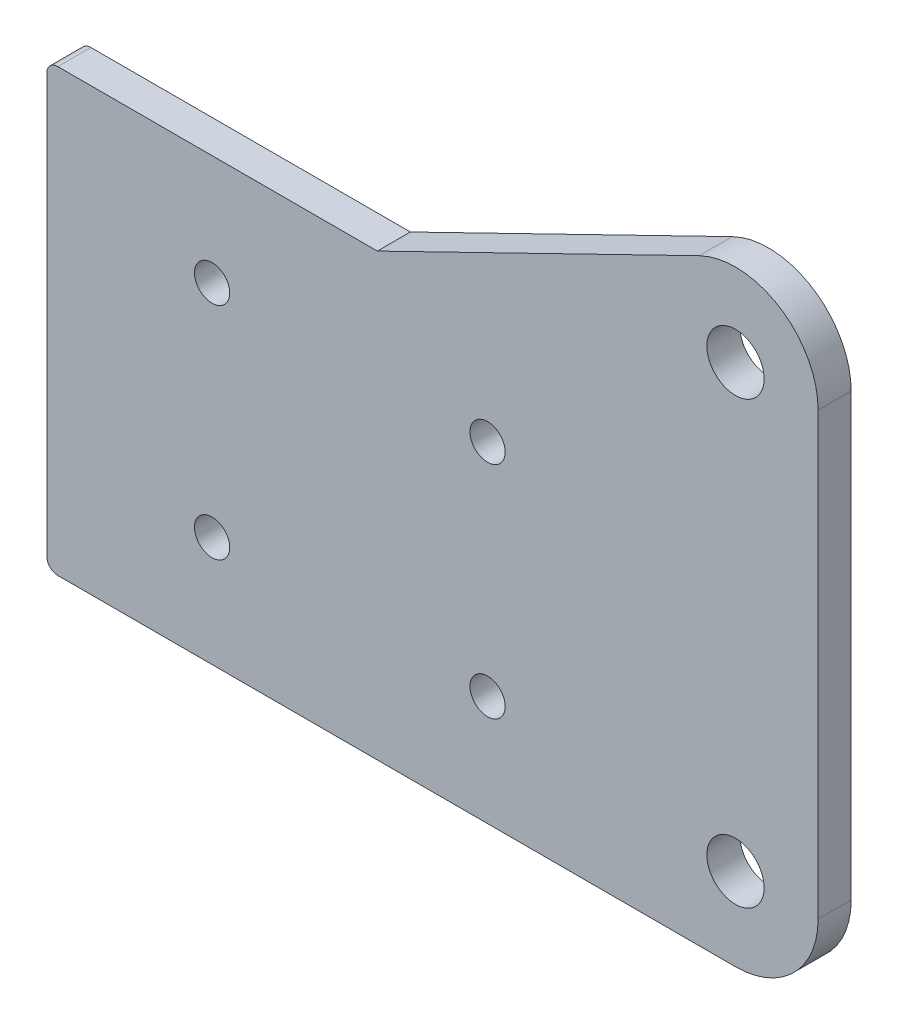
SolidWorks part; units mm, degrees
ref_plane "前视基准面" through (0, 0, 0) normal (0, 0, 1) x (1, 0, 0)
ref_plane "上视基准面" through (0, 0, 0) normal (0, 1, 0) x (1, 0, 0)
ref_plane "右视基准面" through (0, 0, 0) normal (1, 0, 0) x (0, 0, -1)
sketch "草图1" plane through (0, 0, 0) normal (0, 0, 1) x (1, 0, 0)
  line L0 (0, 0) -> (50000, 0) construction
  line L1 (-35, -27.5) -> (27.5, -27.5)
  line L2 (-35, -27.5) -> (-35, 27.5)
  line L3 (-35, 27.5) -> (27.5, 27.5)
  line L4 (35, -20) -> (35, 20)
  line L5 (-35, -27.5) -> (35, 27.5) construction
  line L6 (-35, 27.5) -> (35, -27.5) construction
  circle A0 centre (27.5, 20) radius 2.6
  circle A1 centre (27.5, -20) radius 2.6
  arc A4 (27.5, -27.5) -> (35, -20) centre (27.5, -20) ccw
  arc A5 (27.5, 27.5) -> (35, 20) centre (27.5, 20) cw
  point P0 (0, 0)
  dimension "D1" = 5.2
  dimension "D5" = 7.5
  dimension "D2" = 70
  dimension "60" = 55
  dimension "D3" = 40
  dimension "D4" = 7.5
extrude "凸台-拉伸1" add sketch "草图1" along normal blind 3
sketch "草图2" plane through (0, 0, 3) normal (0, 0, 1) x (1, 0, 0)
  line L0 (-35, 12.5) -> (-5, 12.5)
  line L1 (-35, 27.5) -> (-35, -27.5) construction
  line L2 (-5, 12.5) -> (24.2135, 26.7416)
  line L3 (-35, -27.5) -> (27.5, -27.5) construction
  line L4 (-35, 12.5) -> (-35, 37.5)
  line L5 (-35, 37.5) -> (27.5, 37.5)
  line L6 (27.5, 37.5) -> (27.5, 27.5)
  circle A0 centre (27.5, 20) radius 7.5 construction
  arc A1 (24.2135, 26.7416) -> (27.5, 27.5) centre (27.5, 20) cw
  dimension "D1" = 15
  dimension "D4" = 10
  dimension "D2" = 40
  dimension "D3" = 30
extrude "切除-拉伸1" cut sketch "草图2" against normal blind 3
sketch "草图3" plane through (0, 0, 3) normal (0, 0, 1) x (1, 0, 0)
  line L0 (-35, 12.5) -> (-35, -27.5) construction
  line L1 (-20, -17.5) -> (5, -17.5) construction
  line L2 (-20, -17.5) -> (-20, 2.5) construction
  line L3 (-20, 2.5) -> (5, 2.5) construction
  line L4 (5, -17.5) -> (5, 2.5) construction
  line L5 (-20, -17.5) -> (5, 2.5) construction
  line L6 (-20, 2.5) -> (5, -17.5) construction
  line L7 (-20, -7.5) -> (5, -7.5) construction
  line L8 (-35, -27.5) -> (27.5, -27.5) construction
  line L9 (-7.5, 2.5) -> (-7.5, -17.5) construction
  circle A0 centre (-20, 2.5) radius 1.6
  circle A2 centre (5, 2.5) radius 1.6
  circle A3 centre (5, -17.5) radius 1.6
  circle A4 centre (-20, -17.5) radius 1.6
  circle A5 centre (27.5, 20) radius 15 construction
  circle A6 centre (27.5, -20) radius 15 construction
  point P0 (-7.5, -7.5)
  dimension "D4" = 3.2
  dimension "D5" = 10
  dimension "D6" = 30
  dimension "D7" = 30
  dimension "D1" = 20
  dimension "D2" = 25
  dimension "D3" = 15
extrude "切除-拉伸2" cut sketch "草图3" against normal blind 3
fillet "圆角1" radius 1 2 edges at (-35, -27.5, 1.5) (-35, 12.5, 1.5)
